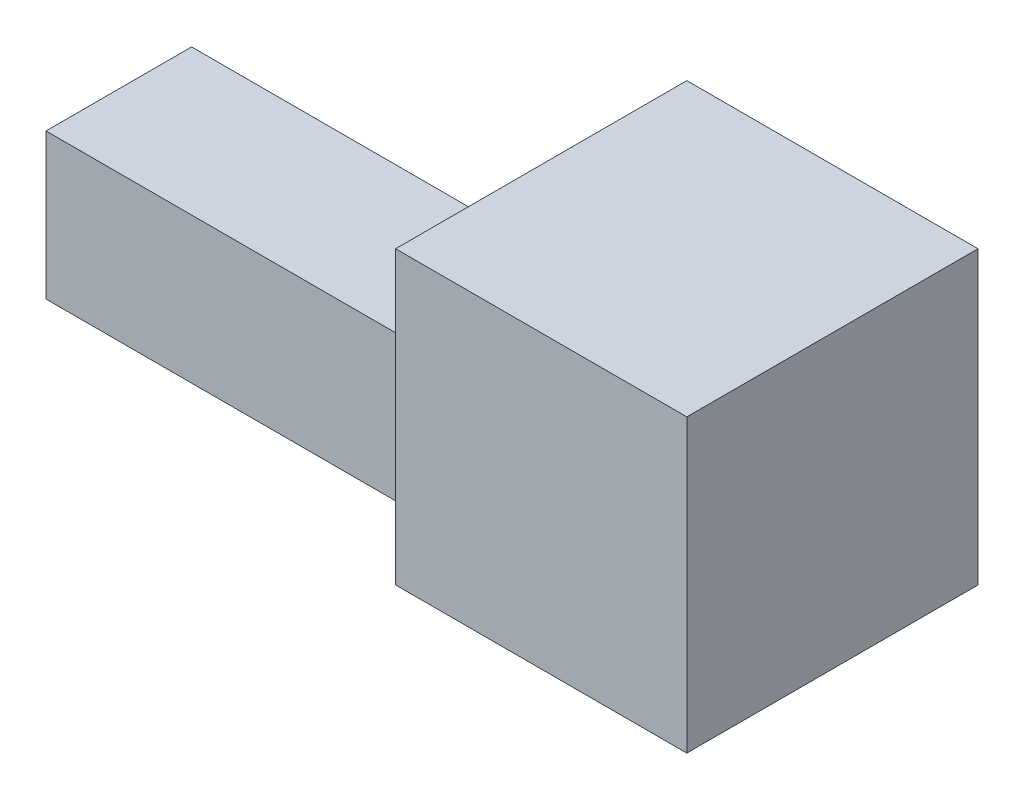
SolidWorks part; units mm, degrees
ref_plane "Front Plane" through (0, 0, 0) normal (0, 0, 1) x (1, 0, 0)
ref_plane "Top Plane" through (0, 0, 0) normal (0, 1, 0) x (1, 0, 0)
ref_plane "Right Plane" through (0, 0, 0) normal (1, 0, 0) x (0, 0, -1)
sketch "Sketch1" plane through (0, 0, 0) normal (0, 1, 0) x (1, 0, 0)
  line L1 (15, -5) -> (-15, -5)
  line L2 (15, -5) -> (15, 5)
  line L3 (15, 5) -> (-15, 5)
  line L4 (-15, -5) -> (-15, 5)
  line L5 (15, -5) -> (-15, 5) construction
  line L6 (15, 5) -> (-15, -5) construction
  point P0 (0, 0)
  dimension "D1" = 30
  dimension "D2" = 10
sketch "Sketch3" plane through (0, 0, 0) normal (0, 1, 0) x (1, 0, 0)
  line L1 (34.0141, -10) -> (14.0141, -10)
  line L2 (34.0141, -10) -> (34.0141, 10)
  line L3 (34.0141, 10) -> (14.0141, 10)
  line L4 (14.0141, -10) -> (14.0141, 10)
  line L5 (34.0141, -10) -> (14.0141, 10) construction
  line L6 (34.0141, 10) -> (14.0141, -10) construction
  point P0 (24.0141, 0)
  dimension "D1" = 20
  dimension "D2" = 20
extrude "Boss-Extrude2" add sketch "Sketch3" along normal blind 20
extrude "Boss-Extrude3" add sketch "Sketch1" along normal blind 10
